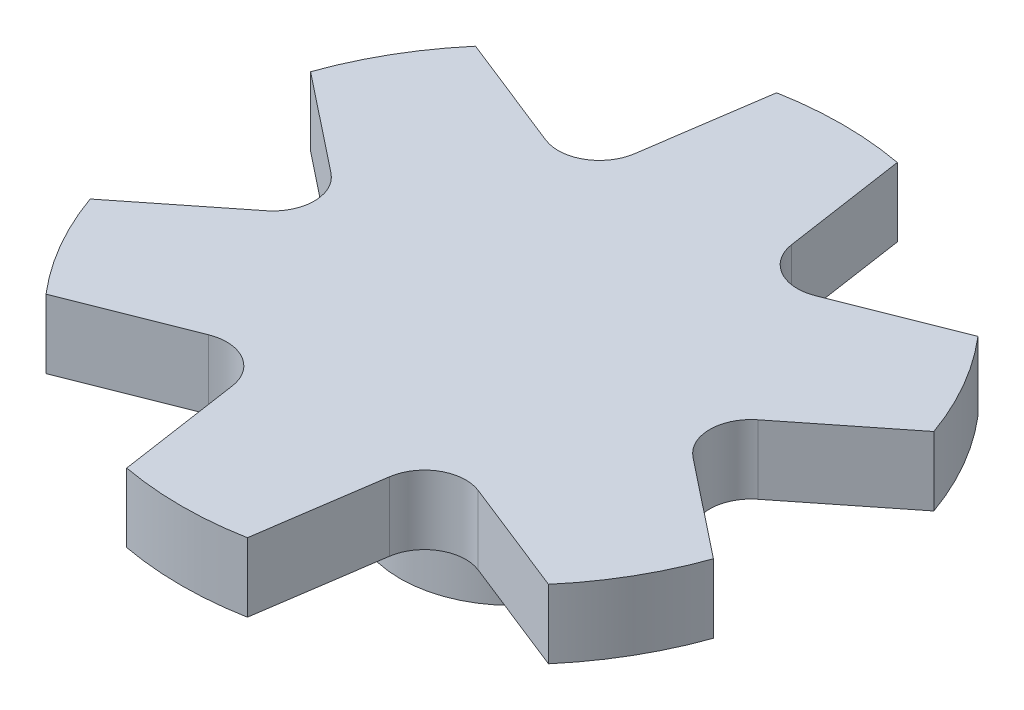
SolidWorks part; units mm, degrees
ref_plane "Спереди" through (0, 0, 0) normal (0, 0, 1) x (1, 0, 0)
ref_plane "Сверху" through (0, 0, 0) normal (0, 1, 0) x (1, 0, 0)
ref_plane "Справа" through (0, 0, 0) normal (1, 0, 0) x (0, 0, -1)
sketch "Эскиз1" plane through (0, 0, 0) normal (0, 1, 0) x (1, 0, 0)
  line L1 (-1.842, -14.158) -> (-2.8557, -7.2972)
  line L2 (1.842, -14.158) -> (2.8557, -7.2972)
  line L3 (-11.3401, -8.6742) -> (-4.8917, -6.1217)
  line L4 (-13.1822, -5.4837) -> (-7.7474, -1.1755)
  line L5 (-13.1822, 5.4837) -> (-7.7474, 1.1755)
  line L6 (-11.3401, 8.6742) -> (-4.8917, 6.1217)
  line L7 (-1.842, 14.158) -> (-2.8557, 7.2972)
  line L8 (1.842, 14.158) -> (2.8557, 7.2972)
  line L9 (11.3401, 8.6742) -> (4.8917, 6.1217)
  line L10 (13.1822, 5.4837) -> (7.7474, 1.1755)
  line L11 (13.1822, -5.4837) -> (7.7474, -1.1755)
  line L12 (11.3401, -8.6742) -> (4.8917, -6.1217)
  arc A0 (-7.7474, -1.1755) -> (-7.7474, 1.1755) centre (-8.6792, 0) ccw
  arc A1 (-2.8557, -7.2972) -> (-4.8917, -6.1217) centre (-4.3396, -7.5164) ccw
  arc A2 (-1.842, -14.158) -> (1.842, -14.158) centre (0, -14.158) ccw
  arc A3 (-4.8917, 6.1217) -> (-2.8557, 7.2972) centre (-4.3396, 7.5164) ccw
  arc A4 (-13.1822, -5.4837) -> (-11.3401, -8.6742) centre (-12.2611, -7.079) ccw
  arc A5 (-11.3401, 8.6742) -> (-13.1822, 5.4837) centre (-12.2611, 7.079) ccw
  arc A6 (1.842, 14.158) -> (-1.842, 14.158) centre (0, 14.158) ccw
  arc A7 (13.1822, 5.4837) -> (11.3401, 8.6742) centre (12.2611, 7.079) ccw
  arc A8 (11.3401, -8.6742) -> (13.1822, -5.4837) centre (12.2611, -7.079) ccw
  arc A9 (4.8917, -6.1217) -> (2.8557, -7.2972) centre (4.3396, -7.5164) ccw
  arc A10 (7.7474, 1.1755) -> (7.7474, -1.1755) centre (8.6792, 0) ccw
  arc A11 (2.8557, 7.2972) -> (4.8917, 6.1217) centre (4.3396, 7.5164) ccw
  dimension "D1" = 1.5
  dimension "D2" = 1.5
extrude "Вытянуть1" add sketch "Эскиз1" along normal blind 2.5
sketch "Эскиз2" plane through (0, 0, 0) normal (0, -1, 0) x (1, 0, 0)
  circle A0 centre (0, 0) radius 4.064
  circle A1 centre (0, 0) radius 2.54
extrude "Вытянуть2" add sketch "Эскиз2" along normal blind 3.75
sketch "Эскиз3" plane through (0, 2.5, 0) normal (0, 1, 0) x (-1, 0, 0)
  circle A0 centre (0, 0) radius 12
  circle A1 centre (0, 0) radius 18.8875
extrude "Вытянуть3" cut sketch "Эскиз3" against normal through all
